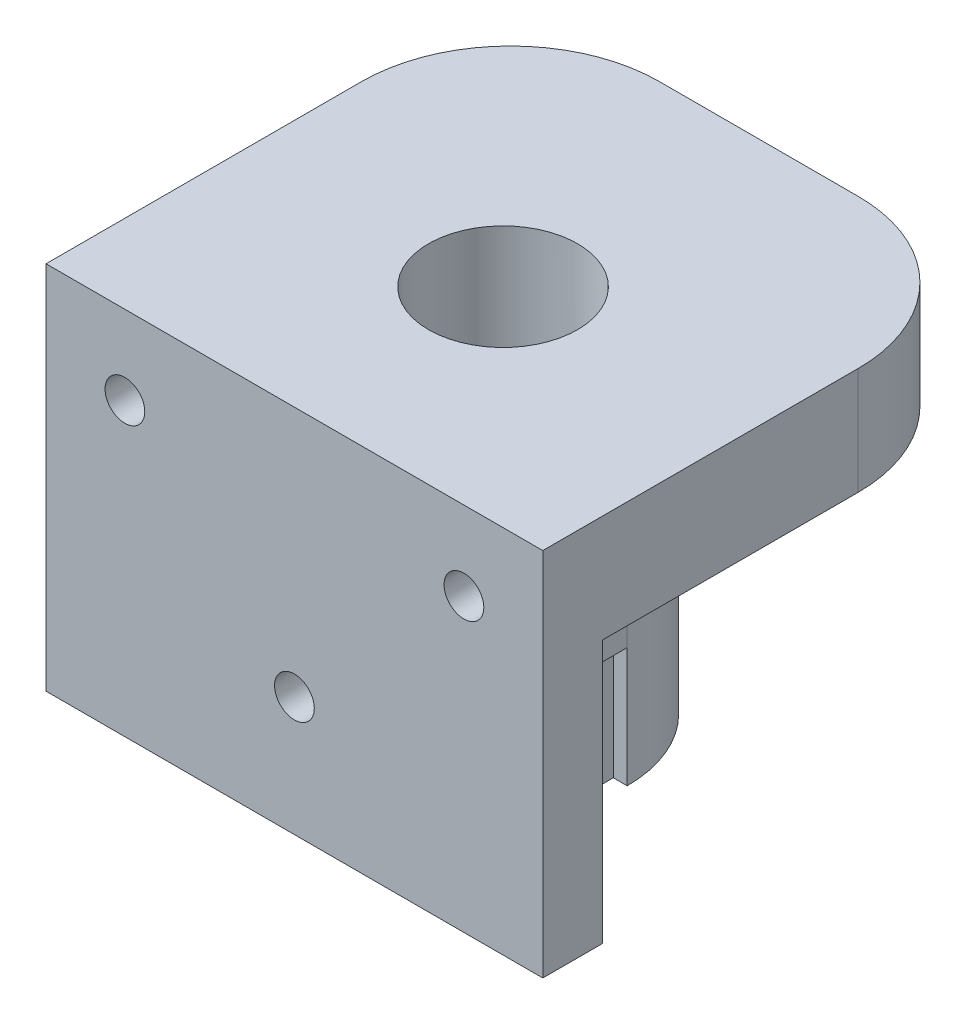
SolidWorks part; units mm, degrees
ref_plane "Front Plane" through (0, 0, 0) normal (0, 0, 1) x (1, 0, 0)
ref_plane "Top Plane" through (0, 0, 0) normal (0, 1, 0) x (1, 0, 0)
ref_plane "Right Plane" through (0, 0, 0) normal (1, 0, 0) x (0, 0, -1)
sketch "Profile-Sketch1" plane through (0, 0, 0) normal (0, 1, 0) x (1, 0, 0)
  line L0 (-25, -21) -> (25, -21)
  line L1 (25, -21) -> (25, -15)
  line L2 (-25, -21) -> (-25, -15)
  line L3 (-25, -15) -> (-22.5, -15)
  line L4 (-12.5, -5) -> (-12.5, 0)
  line L5 (25, -15) -> (22.5, -15)
  line L6 (12.5, -5) -> (12.5, 0)
  circle A0 centre (0, 0) radius 7.5
  arc A6 (12.5, 0) -> (-12.5, 0) centre (0, 0) ccw
  arc A7 (22.5, -15) -> (12.5, -5) centre (22.5, -5) cw
  arc A8 (-12.5, -5) -> (-22.5, -15) centre (-22.5, -5) cw
  dimension "D1" = 15
  dimension "D2" = 12.5
  dimension "D7" = 10
  dimension "D3" = 50
  dimension "D4" = 25
  dimension "D5" = 21
  dimension "D6" = 6
extrude "Profile-Boss-Extrude2" add sketch "Profile-Sketch1" along normal blind 37.2599
sketch "FasteningHoleSketch3" plane through (0, 0, 21) normal (0, 0, 1) x (1, 0, 0)
  line L0 (25, 37.2599) -> (25, 0) construction
  line L1 (-25, 37.2599) -> (-25, 0) construction
  line L2 (-25, 0) -> (25, 0) construction
  circle A2 centre (-17.0625, 29.3224) radius 2
  circle A3 centre (17.0625, 29.3224) radius 2
  dimension "D3" = 4
  dimension "D6" = 7.9375
  dimension "D2" = 29.3224
  dimension "D1" = 7.9375
extrude "FasteningHoleCut-Extrude8" cut sketch "FasteningHoleSketch3" against normal through all
sketch "LM8UUFasteningHoleSketch5" plane through (0, 0, 21) normal (0, 0, 1) x (1, 0, 0)
  line L0 (25, 37.2599) -> (25, 0) construction
  line L1 (-25, 0) -> (25, 0) construction
  line L2 (-25, 37.2599) -> (25, 37.2599) construction
  circle A0 centre (0, 12) radius 2
  circle A1 centre (-17.0625, 29.3224) radius 2 construction
  dimension "D1" = 25
  dimension "D2" = 12
  dimension "D3" = 25.2599
extrude "LM8UUFasteningHoleCut-Extrude9" cut sketch "LM8UUFasteningHoleSketch5" against normal through all
sketch "Sketch1" plane through (0, 0, 0) normal (0, -1, 0) x (1, 0, 0)
  line L0 (13.9, 12.85) -> (16.3638, 12.85)
  line L1 (11.1, 12.85) -> (13.9, 12.85)
  line L2 (11.1, 12.85) -> (11.1, 0)
  line L3 (11.1, 0) -> (13.9, 0)
  line L4 (13.9, 10.1029) -> (13.9, 0)
  line L5 (16.3638, 12.85) -> (13.9, 10.1029)
  arc A0 (22.5, 15) -> (12.5, 5) centre (22.5, 5) ccw construction
  dimension "D2" = 12.85
  dimension "D3" = 2.8
  dimension "D1" = 1.4
extrude "YAxisMicroSwitchCut-Extrude1" cut sketch "Sketch1" against normal blind 12.05
sketch "MicroSwitchMountingHoleSketch2" plane through (11.1, 0, 0) normal (1, 0, 0) x (0, 0, -1)
  line L0 (-12.85, 0) -> (-12.85, 12.05) construction
  line L1 (0, 12.05) -> (0, 0) construction
  line L3 (-12.85, 12.05) -> (-5, 12.05) construction
  circle A0 centre (-9.6, 5.05) radius 1.5
  circle A1 centre (-3.25, 5.05) radius 1.5
  dimension "D1" = 3
  dimension "D2" = 3.25
  dimension "D3" = 3.25
  dimension "D4" = 7
extrude "YAxisMicroSwitchMountingHoleCut-Extrude2" cut sketch "MicroSwitchMountingHoleSketch2" against normal blind 3.1
sketch "TopKnotchSketch2" plane through (0, 37.2599, 0) normal (0, 1, 0) x (1, 0, 0)
  line L0 (-25, -15) -> (25, -15)
  line L1 (-25, -15) -> (-25, 12.5)
  line L2 (25, -15) -> (25, 12.5)
  line L3 (-25, 12.5) -> (25, 12.5)
  line L4 (-25, -15) -> (-25, -21) construction
  arc A0 (12.5, 0) -> (-12.5, 0) centre (0, 0) ccw construction
extrude "TopKnotchCut-Extrude1" cut sketch "TopKnotchSketch2" against normal blind 10.8
sketch "TopShelfSketch3" plane through (0, 0, 15) normal (0, 0, -1) x (-1, 0, 0)
  line L0 (-25, 37.2599) -> (-25, 0) construction
  line L1 (-25, 37.2599) -> (25, 37.2599)
  line L2 (-25, 37.2599) -> (-25, 26.4599)
  line L3 (-25, 26.4599) -> (25, 26.4599)
  line L4 (25, 37.2599) -> (25, 26.4599)
  line L6 (22.5, 26.4599) -> (-22.5, 26.4599) construction
  line L7 (25, 37.2599) -> (25, 0) construction
  line L8 (-25, 37.2599) -> (25, 37.2599) construction
extrude "TopShelfBoss-Extrude1" add sketch "TopShelfSketch3" along normal blind 40.75
sketch "TopShelfLM8UUHoleSketch" plane through (0, 37.2599, 0) normal (0, 1, 0) x (1, 0, 0)
  circle A0 centre (0, 0) radius 7.5
  circle A1 centre (0, 0) radius 7.5 construction
extrude "TopShelfLM8UUCut-Extrude2" cut sketch "TopShelfLM8UUHoleSketch" against normal through all
sketch "XAxisMicroSwitchSketch7" plane through (0, 26.4599, 0) normal (0, -1, 0) x (1, 0, 0)
  line L0 (25, -25.75) -> (-25, -25.75) construction
  line L1 (-6.425, -13.7) -> (6.425, -13.7)
  line L2 (-6.425, -13.7) -> (-6.425, -25.75)
  line L3 (-6.425, -25.75) -> (6.425, -25.75)
  line L4 (6.425, -13.7) -> (6.425, -25.75)
  line L5 (-25, -25.75) -> (-25, 15) construction
  dimension "D2" = 12.85
  dimension "D1" = 12.05
  dimension "D3" = 18.575
extrude "XAxisMicroSwitchCut-Extrude5" cut sketch "XAxisMicroSwitchSketch7" against normal blind 2.8
sketch "XAxisMicroSwitchMountingHoleSketch8" plane through (0, 29.2599, 0) normal (0, -1, 0) x (1, 0, 0)
  line L0 (6.425, -13.7) -> (-6.425, -13.7) construction
  line L1 (-6.425, -13.7) -> (-6.425, -25.75) construction
  line L2 (6.425, -25.75) -> (6.425, -13.7) construction
  circle A0 centre (-3.175, -20.7) radius 1.5
  circle A1 centre (3.175, -20.7) radius 1.5
  point P8 (-6.425, -19.725)
  dimension "D2" = 3.25
  dimension "D3" = 3.25
  dimension "D4" = 3
  dimension "D1" = 7
extrude "XAxisMicroSwitchMountingHoleCut-Extrude6" cut sketch "XAxisMicroSwitchMountingHoleSketch8" against normal blind 3.1
fillet "Fillet3" radius 15 1 edges at (25, 31.8599, -25.75)
fillet "Fillet4" radius 15 1 edges at (-25, 31.8599, -25.75)
equation "\"RailThickness\"= .125in'Spec"
equation "\"LM8UUDiameter\"= 15mm"
equation "\"MidLeftOrRightSideRailHeight\"= 2.0in"
equation "\"RodStabilizerLength\"= 50mm"
equation "\"HoleOffsetFromEdge\"= \"RailThickness\" * 2.5"
equation "\"StepperMountingHoleOffsetFromItsSide\"= 5.5mm'Spec"
equation "\"StepperMountingHoleOffsetFromLeftOrRightSide\"= \"StepperMountingHoleOffsetFromItsSide\" + \"RailThickness\""
equation "\"StepperMountingHoleDistance\"= 31mm'Spec"
equation "\"LM8UUHeight\"= 24mm'Spec"
equation "\"ZAxisLeadScrewLength\"= 200mm"
equation "\"LegHeight\"= 70mm'Space needed for PSU/Stepper/Electronics"
equation "\"V1 BottomOfLowerRail\"= \"LegHeight\""
equation "\"StepperShaftLength\"= 24mm'Pulley will be attached to the end"
equation "\"V2 ToBedAtTopOfZAxis\"= \"V1 BottomOfLowerRail\" - \"LowerEnclosureThickness\" + \"StepperShaftLength\" + \"ZAxisLeadScrewLength\" - \"LM8UUHeight\" / 2'Equals 277"
equation "\"HotEndToTopOfXAxisGB\"= 71.68487mm'Equals 71.68487. Measured after installed onto X-Axis linear rail guide block"
equation "\"TopOfGBToBottomOfLinearRail\"= \"LinearGBWidth\" / 2 + \"LinearRailWidth\" / 2'Equals 19.5"
equation "\"LinearGBWidth\"= 27mm'Spec"
equation "\"V5 ToBottomOfXAxisLinearRail\"= \"V4 ToTopOfBuildPlate/HotEndTip\" + \"HotEndToTopOfXAxisGB\" - \"TopOfGBToBottomOfLinearRail\"'Equals 352.18487"
equation "\"LinearRailWidth\"= 12mm'Spec"
equation "\"V6 ToMiddleOfYAxisGantryBlock\"= \"V5 ToBottomOfXAxisLinearRail\" - \"GABHeight\" / 2'Equals 334.18487"
equation "\"GABUpperHeight\"= 4mm"
equation "\"GABMidWallHeight\"= 28mm'Must equal 28 or changes alignment"
equation "\"BedToBuildPlateStandoffLength\"= 15mm"
equation "\"BuildPlateHeight\"= 8mm'Spec"
equation "\"V4 ToTopOfBuildPlate/HotEndTip\"= \"V2 ToBedAtTopOfZAxis\" + \"BedToBuildPlateStandoffLength\" + \"BuildPlateHeight\""
equation "\"RodStabilizerHeight\"= \"V8 ToBottomOfMidSideRail\" - \"V2 ToBedAtTopOfZAxis\" + \"HoleOffsetFromEdge\" * 2"
equation "\"LowerEnclosureThickness\"= 5mm"
equation "\"D1@Profile-Sketch1\" = \"LM8UUDiameter\""
equation "\"D3@Profile-Sketch1\" = \"RodStabilizerLength\""
equation "\"D4@Profile-Sketch1\" = \"RodStabilizerLength\" / 2"
equation "\"RodStabilizerWidthFromMidRailToZAxisRodCenter\"= \"StepperMountingHoleOffsetFromLeftOrRightSide\" + \"StepperMountingHoleDistance\" / 2 - \"RailThickness\""
equation "\"StandardWallThickness\"= 3mm"
equation "\"D6@Profile-Sketch1\" = \"StandardWallThickness\" * 2"
equation "\"D1@Profile-Boss-Extrude2\"= \"RodStabilizerHeight\""
equation "\"D6@FasteningHoleSketch3\"=\"HoleOffsetFromEdge\""
equation "\"D2@LM8UUFasteningHoleSketch5\"=\"LM8UUHeight\"/2"
equation "\"V8 ToTopOfMidSideRail\"= \"V6 ToMiddleOfYAxisGantryBlock\" + \"MidSideRailVerticalOffset\"'Equals 349.18487"
equation "\"D5@Profile-Sketch1\"=\"RodStabilizerWidthFromMidRailToZAxisRodCenter\""
equation "\"RodStabilizerMountingHoleYOffsetFromBottom\"= \"RodStabilizerHeight\" - \"HoleOffsetFromEdge\""
equation "\"D2@FasteningHoleSketch3\"=\"RodStabilizerMountingHoleYOffsetFromBottom\""
equation "\"D3@FasteningHoleSketch3\"=\"M3HeatInsertHoleDiameter\""
equation "\"GABLowerHeight\"= 4mm"
equation "\"GABHeight\"= \"GABLowerHeight\" + \"GABMidWallHeight\" + \"GABUpperHeight\""
equation "\"V8 ToBottomOfMidSideRail\"= \"V8 ToTopOfMidSideRail\" - \"MidLeftOrRightSideRailHeight\"'Equals 298.38487"
equation "\"D1@LM8UUFasteningHoleSketch5\"=\"RodStabilizerLength\"/2"
equation "\"MidSideRailVerticalOffset\"= \"LinearRailWidth\" + 3mm'Allows space for RodStabilizer to attach to bottom of MidSideRail"
equation "\"M3HeatInsertHoleDiameter\"= 4mm'Spec"
equation "\"MicroSwitchLength\"= 12.85mm"
equation "\"MicroSwitchHeight\"= 6.55mm"
equation "\"MicroSwitchMountHoleOffsetFromSide\"= 3.25mm"
equation "\"MicroSwitchDepth\"= 2.8mm"
equation "\"MicroSwitchTerminalHeight\"= 3.5mm"
equation "\"D2@Sketch1\"=\"MicroSwitchLength\""
equation "\"D3@Sketch1\"=\"MicroSwitchDepth\""
equation "\"D1@Sketch1\"=\"MicroSwitchDepth\"/2"
equation "\"D1@YAxisMicroSwitchCut-Extrude1\" = \"MicroSwitchHeight\" + \"MicroSwitchTerminalHeight\" + \"MicroSwitchExtraMountingHeight\""
equation "\"M2HeatInsertHoleDiameter\"= 3mm'Spec"
equation "\"D1@MicroSwitchMountingHoleSketch2\" = \"M2HeatInsertHoleDiameter\""
equation "\"D2@MicroSwitchMountingHoleSketch2\" = \"MicroSwitchMountHoleOffsetFromSide\""
equation "\"D3@MicroSwitchMountingHoleSketch2\" = \"MicroSwitchMountHoleOffsetFromSide\""
equation "\"MicroSwitchMountHoleOffsetFromBottom\"= 1.5mm"
equation "\"D4@MicroSwitchMountingHoleSketch2\"= \"MicroSwitchTerminalHeight\" + \"MicroSwitchExtraMountingHeight\" + \"MicroSwitchMountHoleOffsetFromBottom\""
equation "\"D1@YAxisMicroSwitchMountingHoleCut-Extrude2\" = \"M2HeatInsertHoleDepth\""
equation "\"MicroSwitchExtraMountingHeight\"= 2mm"
equation "\"M2HeatInsertHoleDepth\"= 3.1mm'Spec"
equation "\"GABDistanceFromBackToFirstPulley\"= 13.5mm"
equation "\"GABPulleyDDistanceBetween\"= 12.5mm'From the100"
equation "\"GABDistanceFromPulleyToFront\"= 8mm"
equation "\"GABDepth\"= \"GABDistanceFromBackToFirstPulley\" + \"GABPulleyDDistanceBetween\" + \"GABDistanceFromPulleyToFront\""
equation "\"LinearGBWithRailDepth\"= 12.75mm'Spec"
equation "\"GABDepthPlusLinearRail\"= \"GABDepth\" + \"LinearGBWithRailDepth\""
equation "\"D1@TopKnotchCut-Extrude1\" = \"MicroSwitchDepth\" + 8mm"
equation "\"D1@TopShelfBoss-Extrude1\" = \"GABDepthPlusLinearRail\" - \"StandardWallThickness\" * 2"
equation "\"D1@XAxisMicroSwitchSketch7\" = \"MicroSwitchHeight\" + \"MicroSwitchTerminalHeight\" + 2mm"
equation "\"D2@XAxisMicroSwitchSketch7\" = \"MicroSwitchLength\""
equation "\"D3@XAxisMicroSwitchSketch7\" =  ( \"RodStabilizerLength\" - \"MicroSwitchLength\" )  / 2"
equation "\"D1@XAxisMicroSwitchCut-Extrude5\" = \"MicroSwitchDepth\""
equation "\"D1@XAxisMicroSwitchMountingHoleSketch8\" = \"MicroSwitchMountHoleOffsetFromBottom\" + \"MicroSwitchTerminalHeight\" + 2mm"
equation "\"D2@XAxisMicroSwitchMountingHoleSketch8\" = \"MicroSwitchMountHoleOffsetFromSide\""
equation "\"D3@XAxisMicroSwitchMountingHoleSketch8\" = \"MicroSwitchMountHoleOffsetFromSide\""
equation "\"D4@XAxisMicroSwitchMountingHoleSketch8\" = \"M2HeatInsertHoleDiameter\""
equation "\"D1@XAxisMicroSwitchMountingHoleCut-Extrude6\" = \"M2HeatInsertHoleDepth\""
equation "\"D1@Fillet3\"=\"LM8UUDiameter\""
equation "\"D1@Fillet4\"=\"LM8UUDiameter\""
